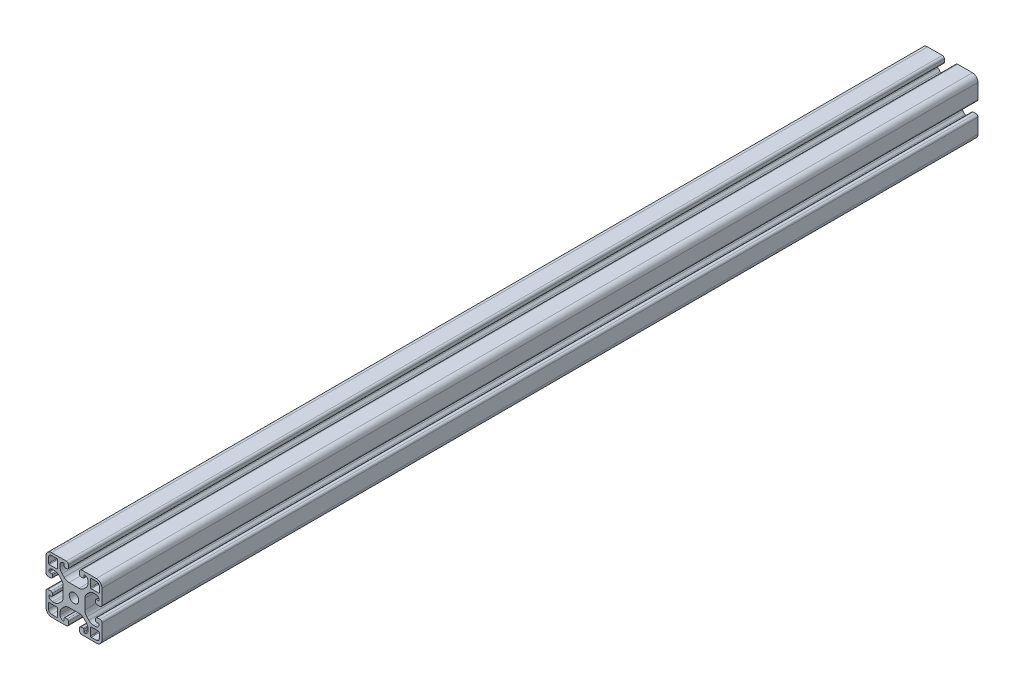
SolidWorks part; units mm, degrees
ref_plane "Plan de face" through (0, 0, 0) normal (0, 0, 1) x (1, 0, 0)
ref_plane "Plan de dessus" through (0, 0, 0) normal (0, 1, 0) x (1, 0, 0)
ref_plane "Plan de droite" through (0, 0, 0) normal (1, 0, 0) x (0, 0, -1)
ref_plane "Plan1" through (0, 0, -30) normal (0, 0, -1) x (-1, 0, 0)
sketch "Esquisse1" plane through (0, 0, -30) normal (0, 0, -1) x (-1, 0, 0)
  line B0 (-4.5, 15) -> (-4.5, 13.5)
  line B1 (-4, 13) -> (-2.5, 13)
  line B2 (-4.5, 10) -> (-5.8076, 10)
  line B3 (-9.3431, 11.4645) -> (-10.7855, 12.9069)
  line B4 (-12.25, 16.4424) -> (-12.25, 23.5576)
  line B5 (-10.7855, 27.0931) -> (-9.3431, 28.5355)
  line B6 (-5.8076, 30) -> (-4.5, 30)
  line B7 (-2.5, 27) -> (-4, 27)
  line B8 (-4.5, 26.5) -> (-4.5, 25)
  line B9 (-3.5, 24) -> (-1.5, 24)
  line B10 (0, 25.5) -> (0, 36)
  line B11 (-4, 40) -> (-14.5, 40)
  line B12 (-16, 38.5) -> (-16, 36.5)
  line B13 (-15, 35.5) -> (-13.5, 35.5)
  line B14 (-13, 36) -> (-13, 37.5)
  line B15 (-10, 35.5) -> (-10, 34.1924)
  line B16 (-11.4645, 30.6569) -> (-12.9069, 29.2145)
  line B17 (-16.4424, 27.75) -> (-23.5576, 27.75)
  line B18 (-27.0931, 29.2145) -> (-28.5355, 30.6569)
  line B19 (-30, 34.1924) -> (-30, 35.5)
  line B20 (-27, 37.5) -> (-27, 36)
  line B21 (-26.5, 35.5) -> (-25, 35.5)
  line B22 (-24, 36.5) -> (-24, 38.5)
  line B23 (-25.5, 40) -> (-36, 40)
  line B24 (-40, 36) -> (-40, 25.5)
  line B25 (-38.5, 24) -> (-36.5, 24)
  line B26 (-35.5, 25) -> (-35.5, 26.5)
  line B27 (-36, 27) -> (-37.5, 27)
  line B28 (-35.5, 30) -> (-34.1924, 30)
  line B29 (-30.6569, 28.5355) -> (-29.2145, 27.0931)
  line B30 (-27.75, 23.5576) -> (-27.75, 16.4424)
  line B31 (-29.2145, 12.9069) -> (-30.6569, 11.4645)
  line B32 (-34.1924, 10) -> (-35.5, 10)
  line B33 (-37.5, 13) -> (-36, 13)
  line B34 (-35.5, 13.5) -> (-35.5, 15)
  line B35 (-36.5, 16) -> (-38.5, 16)
  line B36 (-40, 14.5) -> (-40, 4)
  line B37 (-36, 0) -> (-25.5, 0)
  line B38 (-24, 1.5) -> (-24, 3.5)
  line B39 (-25, 4.5) -> (-26.5, 4.5)
  line B40 (-27, 4) -> (-27, 2.5)
  line B41 (-30, 4.5) -> (-30, 5.8076)
  line B42 (-28.5355, 9.3431) -> (-27.0931, 10.7855)
  line B43 (-23.5576, 12.25) -> (-16.4424, 12.25)
  line B44 (-12.9069, 10.7855) -> (-11.4645, 9.3431)
  line B45 (-10, 5.8076) -> (-10, 4.5)
  line B46 (-13, 2.5) -> (-13, 4)
  line B47 (-13.5, 4.5) -> (-15, 4.5)
  line B48 (-16, 3.5) -> (-16, 1.5)
  line B49 (-14.5, 0) -> (-4, 0)
  line B50 (0, 4) -> (0, 14.5)
  line B51 (-1.5, 16) -> (-3.5, 16)
  line B52 (-4, 1.8) -> (-7.7, 1.8)
  line B53 (-8.2, 2.3) -> (-8.2, 7.7)
  line B54 (-7.7, 8.2) -> (-2.3, 8.2)
  line B55 (-1.8, 7.7) -> (-1.8, 4)
  line B56 (-38.2, 4) -> (-38.2, 7.7)
  line B57 (-37.7, 8.2) -> (-32.3, 8.2)
  line B58 (-31.8, 7.7) -> (-31.8, 2.3)
  line B59 (-32.3, 1.8) -> (-36, 1.8)
  line B60 (-36, 38.2) -> (-32.3, 38.2)
  line B61 (-31.8, 37.7) -> (-31.8, 32.3)
  line B62 (-32.3, 31.8) -> (-37.7, 31.8)
  line B63 (-38.2, 32.3) -> (-38.2, 36)
  line B64 (-1.8, 36) -> (-1.8, 32.3)
  line B65 (-2.3, 31.8) -> (-7.7, 31.8)
  line B66 (-8.2, 32.3) -> (-8.2, 37.7)
  line B67 (-7.7, 38.2) -> (-4, 38.2)
  arc B68 (-4.5, 13.5) -> (-4, 13) centre (-4, 13.5) ccw
  arc B69 (-2.5, 13) -> (-2, 12.5) centre (-2.5, 12.5) cw
  arc B70 (-2, 12.5) -> (-4.5, 10) centre (-4.5, 12.5) cw
  arc B71 (-5.8076, 10) -> (-9.3431, 11.4645) centre (-5.8076, 15) cw
  arc B72 (-10.7855, 12.9069) -> (-12.25, 16.4424) centre (-7.25, 16.4424) cw
  arc B73 (-12.25, 23.5576) -> (-10.7855, 27.0931) centre (-7.25, 23.5576) cw
  arc B74 (-9.3431, 28.5355) -> (-5.8076, 30) centre (-5.8076, 25) cw
  arc B75 (-4.5, 30) -> (-2, 27.5) centre (-4.5, 27.5) cw
  arc B76 (-2, 27.5) -> (-2.5, 27) centre (-2.5, 27.5) cw
  arc B77 (-4, 27) -> (-4.5, 26.5) centre (-4, 26.5) ccw
  arc B78 (-4.5, 25) -> (-3.5, 24) centre (-3.5, 25) ccw
  arc B79 (-1.5, 24) -> (0, 25.5) centre (-1.5, 25.5) ccw
  arc B80 (0, 36) -> (-4, 40) centre (-4, 36) ccw
  arc B81 (-14.5, 40) -> (-16, 38.5) centre (-14.5, 38.5) ccw
  arc B82 (-16, 36.5) -> (-15, 35.5) centre (-15, 36.5) ccw
  arc B83 (-13.5, 35.5) -> (-13, 36) centre (-13.5, 36) ccw
  arc B84 (-13, 37.5) -> (-12.5, 38) centre (-12.5, 37.5) cw
  arc B85 (-12.5, 38) -> (-10, 35.5) centre (-12.5, 35.5) cw
  arc B86 (-10, 34.1924) -> (-11.4645, 30.6569) centre (-15, 34.1924) cw
  arc B87 (-12.9069, 29.2145) -> (-16.4424, 27.75) centre (-16.4424, 32.75) cw
  arc B88 (-23.5576, 27.75) -> (-27.0931, 29.2145) centre (-23.5576, 32.75) cw
  arc B89 (-28.5355, 30.6569) -> (-30, 34.1924) centre (-25, 34.1924) cw
  arc B90 (-30, 35.5) -> (-27.5, 38) centre (-27.5, 35.5) cw
  arc B91 (-27.5, 38) -> (-27, 37.5) centre (-27.5, 37.5) cw
  arc B92 (-27, 36) -> (-26.5, 35.5) centre (-26.5, 36) ccw
  arc B93 (-25, 35.5) -> (-24, 36.5) centre (-25, 36.5) ccw
  arc B94 (-24, 38.5) -> (-25.5, 40) centre (-25.5, 38.5) ccw
  arc B95 (-36, 40) -> (-40, 36) centre (-36, 36) ccw
  arc B96 (-40, 25.5) -> (-38.5, 24) centre (-38.5, 25.5) ccw
  arc B97 (-36.5, 24) -> (-35.5, 25) centre (-36.5, 25) ccw
  arc B98 (-35.5, 26.5) -> (-36, 27) centre (-36, 26.5) ccw
  arc B99 (-37.5, 27) -> (-38, 27.5) centre (-37.5, 27.5) cw
  arc B100 (-38, 27.5) -> (-35.5, 30) centre (-35.5, 27.5) cw
  arc B101 (-34.1924, 30) -> (-30.6569, 28.5355) centre (-34.1924, 25) cw
  arc B102 (-29.2145, 27.0931) -> (-27.75, 23.5576) centre (-32.75, 23.5576) cw
  arc B103 (-27.75, 16.4424) -> (-29.2145, 12.9069) centre (-32.75, 16.4424) cw
  arc B104 (-30.6569, 11.4645) -> (-34.1924, 10) centre (-34.1924, 15) cw
  arc B105 (-35.5, 10) -> (-38, 12.5) centre (-35.5, 12.5) cw
  arc B106 (-38, 12.5) -> (-37.5, 13) centre (-37.5, 12.5) cw
  arc B107 (-36, 13) -> (-35.5, 13.5) centre (-36, 13.5) ccw
  arc B108 (-35.5, 15) -> (-36.5, 16) centre (-36.5, 15) ccw
  arc B109 (-38.5, 16) -> (-40, 14.5) centre (-38.5, 14.5) ccw
  arc B110 (-40, 4) -> (-36, 0) centre (-36, 4) ccw
  arc B111 (-25.5, 0) -> (-24, 1.5) centre (-25.5, 1.5) ccw
  arc B112 (-24, 3.5) -> (-25, 4.5) centre (-25, 3.5) ccw
  arc B113 (-26.5, 4.5) -> (-27, 4) centre (-26.5, 4) ccw
  arc B114 (-27, 2.5) -> (-27.5, 2) centre (-27.5, 2.5) cw
  arc B115 (-27.5, 2) -> (-30, 4.5) centre (-27.5, 4.5) cw
  arc B116 (-30, 5.8076) -> (-28.5355, 9.3431) centre (-25, 5.8076) cw
  arc B117 (-27.0931, 10.7855) -> (-23.5576, 12.25) centre (-23.5576, 7.25) cw
  arc B118 (-16.4424, 12.25) -> (-12.9069, 10.7855) centre (-16.4424, 7.25) cw
  arc B119 (-11.4645, 9.3431) -> (-10, 5.8076) centre (-15, 5.8076) cw
  arc B120 (-10, 4.5) -> (-12.5, 2) centre (-12.5, 4.5) cw
  arc B121 (-12.5, 2) -> (-13, 2.5) centre (-12.5, 2.5) cw
  arc B122 (-13, 4) -> (-13.5, 4.5) centre (-13.5, 4) ccw
  arc B123 (-15, 4.5) -> (-16, 3.5) centre (-15, 3.5) ccw
  arc B124 (-16, 1.5) -> (-14.5, 0) centre (-14.5, 1.5) ccw
  arc B125 (-4, 0) -> (0, 4) centre (-4, 4) ccw
  arc B126 (0, 14.5) -> (-1.5, 16) centre (-1.5, 14.5) ccw
  arc B127 (-3.5, 16) -> (-4.5, 15) centre (-3.5, 15) ccw
  circle B128 centre (-20, 20) radius 3.4
  arc B129 (-1.8, 4) -> (-4, 1.8) centre (-4, 4) cw
  arc B130 (-7.7, 1.8) -> (-8.2, 2.3) centre (-7.7, 2.3) cw
  arc B131 (-8.2, 7.7) -> (-7.7, 8.2) centre (-7.7, 7.7) cw
  arc B132 (-2.3, 8.2) -> (-1.8, 7.7) centre (-2.3, 7.7) cw
  arc B133 (-36, 1.8) -> (-38.2, 4) centre (-36, 4) cw
  arc B134 (-38.2, 7.7) -> (-37.7, 8.2) centre (-37.7, 7.7) cw
  arc B135 (-32.3, 8.2) -> (-31.8, 7.7) centre (-32.3, 7.7) cw
  arc B136 (-31.8, 2.3) -> (-32.3, 1.8) centre (-32.3, 2.3) cw
  arc B137 (-38.2, 36) -> (-36, 38.2) centre (-36, 36) cw
  arc B138 (-32.3, 38.2) -> (-31.8, 37.7) centre (-32.3, 37.7) cw
  arc B139 (-31.8, 32.3) -> (-32.3, 31.8) centre (-32.3, 32.3) cw
  arc B140 (-37.7, 31.8) -> (-38.2, 32.3) centre (-37.7, 32.3) cw
  arc B141 (-4, 38.2) -> (-1.8, 36) centre (-4, 36) cw
  arc B142 (-1.8, 32.3) -> (-2.3, 31.8) centre (-2.3, 32.3) cw
  arc B143 (-7.7, 31.8) -> (-8.2, 32.3) centre (-7.7, 32.3) cw
  arc B144 (-8.2, 37.7) -> (-7.7, 38.2) centre (-7.7, 37.7) cw
sketch_block_instance "Bloc1-1"
sketch_block "Bloc1"
extrude "Boss.-Extru.1" add sketch "Esquisse1" against normal blind 626
